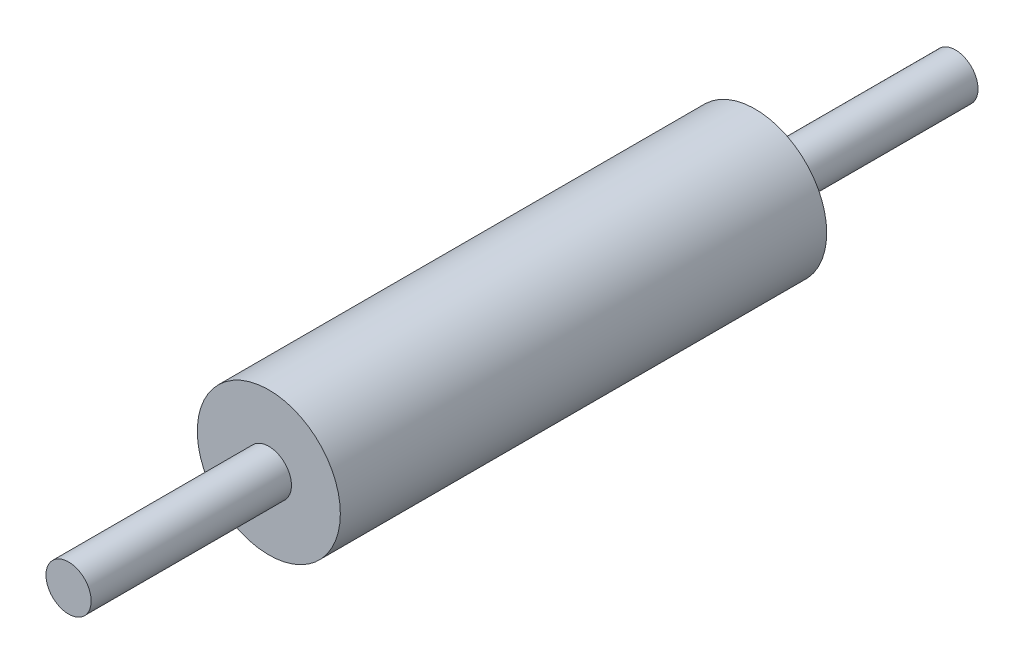
SolidWorks part; units mm, degrees
ref_plane "Front Plane" through (0, 0, 0) normal (0, 0, 1) x (1, 0, 0)
ref_plane "Top Plane" through (0, 0, 0) normal (0, 1, 0) x (1, 0, 0)
ref_plane "Right Plane" through (0, 0, 0) normal (1, 0, 0) x (0, 0, -1)
sketch "Sketch1" plane through (0, 0, 0) normal (0, 0, 1) x (1, 0, 0)
  circle A0 centre (0, 0) radius 12.5
  dimension "D1" = 25
extrude "Boss-Extrude1" add sketch "Sketch1" against normal blind 85
sketch "Sketch2" plane through (0, 0, 0) normal (0, 0, 1) x (1, 0, 0)
  circle A0 centre (0, 0) radius 3.95
  dimension "D1" = 7.9
extrude "Boss-Extrude2" add sketch "Sketch2" along normal blind 35
sketch "Sketch3" plane through (0, 0, -85) normal (0, 0, -1) x (-1, 0, 0)
  circle A0 centre (0, 0) radius 3.95
  dimension "D1" = 7.9
extrude "Boss-Extrude3" add sketch "Sketch3" along normal blind 35
